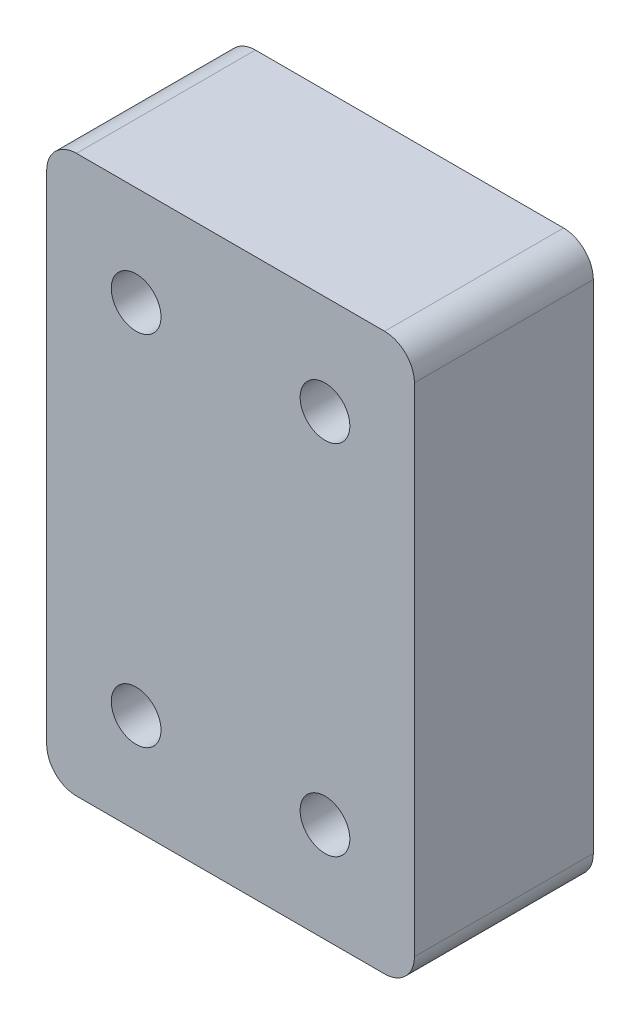
SolidWorks part; units mm, degrees
material "Maple"
ref_plane "Front" through (0, 0, 0) normal (0, 0, 1) x (1, 0, 0)
ref_plane "Top" through (0, 0, 0) normal (0, 1, 0) x (1, 0, 0)
ref_plane "Right" through (0, 0, 0) normal (1, 0, 0) x (0, 0, -1)
sketch "Sketch1" plane through (0, 0, 0) normal (0, 0, 1) x (1, 0, 0)
  line L5 (-15.5, -28) -> (15.5, -28)
  line L6 (-18.5, -25) -> (-18.5, 25)
  line L7 (-15.5, 28) -> (15.5, 28)
  line L8 (18.5, -25) -> (18.5, 25)
  line L9 (-18.5, -28) -> (18.5, 28) construction
  line L10 (-18.5, 28) -> (18.5, -28) construction
  arc A4 (-15.5, -28) -> (-18.5, -25) centre (-15.5, -25) cw
  arc A5 (15.5, -28) -> (18.5, -25) centre (15.5, -25) ccw
  arc A6 (15.5, 28) -> (18.5, 25) centre (15.5, 25) cw
  arc A7 (-18.5, 25) -> (-15.5, 28) centre (-15.5, 25) cw
  point P0 (0, 0)
  dimension "D3" = 3
  dimension "D1" = 37
  dimension "D2" = 56
extrude "Boss-Extrude1" add sketch "Sketch1" along normal blind 18
sketch "Sketch2" plane through (0, 0, 18) normal (0, 0, 1) x (1, 0, 0)
  line L0 (-43.0827, 0) -> (40.1391, 0) construction
  line L6 (-18.5, 25) -> (-18.5, -25) construction
  line L7 (0, 31.8162) -> (0, -46.8362) construction
  circle A0 centre (-9.5, 18) radius 2.5
  circle A1 centre (-9.5, -18) radius 2.5
  circle A2 centre (9.5, -18) radius 2.5
  circle A3 centre (9.5, 18) radius 2.5
  point P0 (0, 0)
  dimension "D3" = 5
  dimension "D1" = 9
  dimension "D4" = 36
extrude "Cut-Extrude1" cut sketch "Sketch2" against normal blind 4
